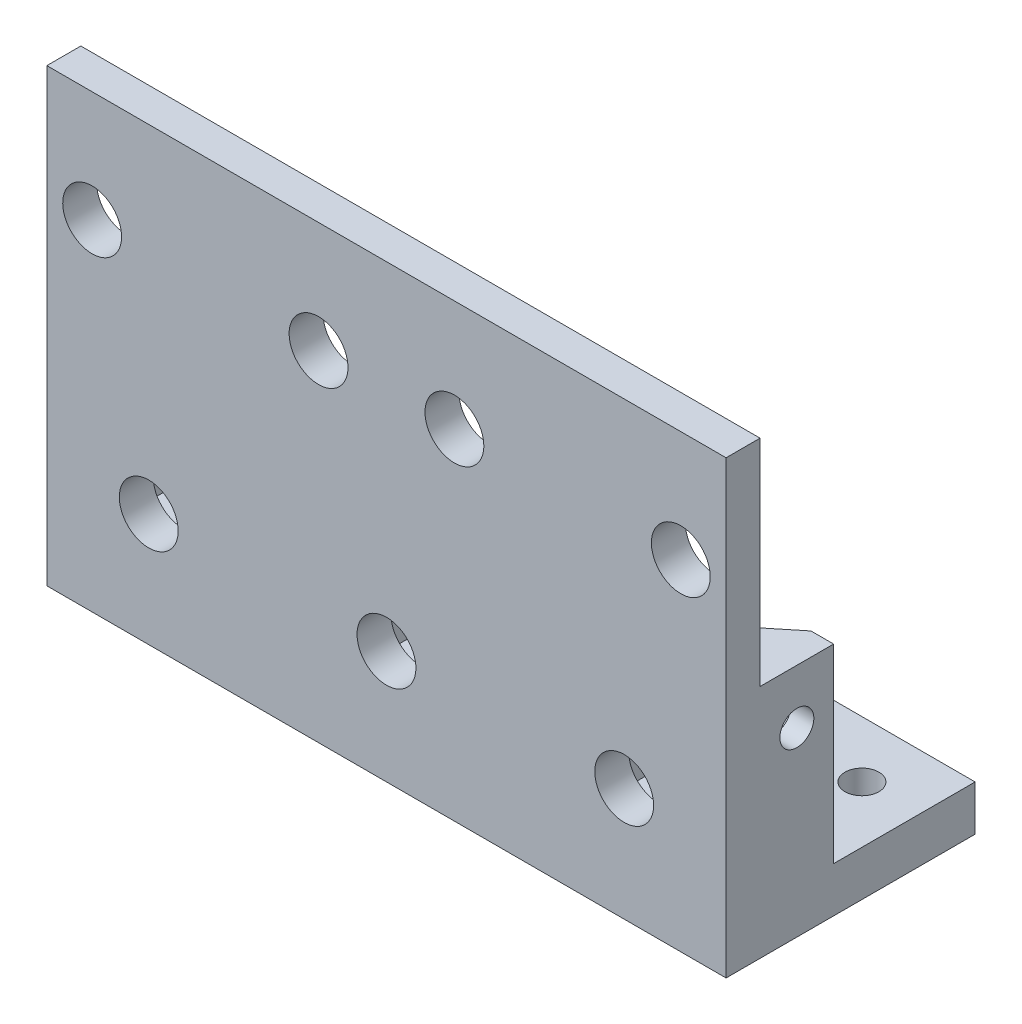
SolidWorks part; units mm, degrees
ref_plane "前视基准面" through (0, 0, 0) normal (0, 0, 1) x (1, 0, 0)
ref_plane "上视基准面" through (0, 0, 0) normal (0, 1, 0) x (1, 0, 0)
ref_plane "右视基准面" through (0, 0, 0) normal (1, 0, 0) x (0, 0, -1)
other "Configuration Table"
sketch "草图1" plane through (0, 0, 0) normal (1, 0, 0) x (0, 0, -1)
  line L1 (-1.5, 19.9) -> (1.5, 19.9)
  line L2 (-1.5, 19.9) -> (-1.5, -19.9)
  line L3 (-1.5, -19.9) -> (1.5, -19.9)
  line L4 (1.5, 19.9) -> (1.5, -0.1)
  line L5 (-1.5, 19.9) -> (1.5, -19.9) construction
  line L6 (-1.5, -19.9) -> (1.5, 19.9) construction
  line L8 (1.5, -19.9) -> (20.5, -19.9)
  line L11 (20.5, -19.9) -> (20.5, -15.9)
  line L12 (20.5, -15.9) -> (1.5, -0.1)
  point P0 (0, 0)
  dimension "D1" = 3
  dimension "D2" = 39.8
  dimension "D3" = 20
  dimension "D4" = 4
  dimension "D5" = 22
extrude "凸台-拉伸1" add sketch "草图1" along normal blind 60
ref_plane "基准面1" through (0, -15.9, 0) normal (0, -1, 0) x (-1, 0, 0)
sketch "草图2" plane through (0, -15.9, 0) normal (0, -1, 0) x (-1, 0, 0)
  line L1 (-60, 20.5) -> (-45, 20.5)
  line L2 (-60, 20.5) -> (-60, 1.5)
  line L3 (-60, 1.5) -> (-45, 1.5)
  line L4 (-45, 20.5) -> (-45, 1.5)
  line L5 (0, 20.5) -> (-15, 20.5)
  line L6 (0, 20.5) -> (0, 1.5)
  line L7 (0, 1.5) -> (-15, 1.5)
  line L8 (-15, 20.5) -> (-15, 1.5)
  line L13 (-30, 20.5) -> (-30, -1.5) construction
  line L14 (-60, 20.5) -> (0, 20.5) construction
  line L15 (-60, 1.5) -> (0, 1.5) construction
  line L16 (-60, -1.5) -> (0, -1.5) construction
  line L18 (-36, 1.5) -> (-24, 1.5)
  line L19 (-36, 1.5) -> (-36, 20.5)
  line L20 (-36, 20.5) -> (-24, 20.5)
  line L21 (-24, 1.5) -> (-24, 20.5)
  line L22 (-36, 1.5) -> (-24, 20.5) construction
  line L23 (-36, 20.5) -> (-24, 1.5) construction
  point P16 (-30, 11)
  dimension "D1" = 15
  dimension "D2" = 12
  dimension "D3" = 15
extrude "切除-拉伸1" cut sketch "草图2" against normal blind 60
hole_wizard "孔1" positions "草图3" profile "草图4" legacy end condition through all
sketch "草图3" plane through (0, 0, -1.5) normal (0, 0, -1) x (-1, 0, 0)
  line L2 (-60, -19.9) -> (0, -19.9) construction
  line L3 (-60, -15.9) -> (-60, 19.9) construction
  line L4 (0, -15.9) -> (0, 19.9) construction
  line L5 (-24, -0.1) -> (-24, -15.9) construction
  point P0 (-51, -9.9)
  point P2 (-30, -9.9)
  point P4 (-9, -9.9)
  dimension "D1" = 10
  dimension "D2" = 10
  dimension "D3" = 10
  dimension "D4" = 9
  dimension "D5" = 9
  dimension "D6" = 6
sketch "草图4" plane through (51, -9.9, -1.5) normal (1, 0, 0) x (0, 1, 0)
  line L0 (0, 0) -> (0, 3)
  line L1 (0, 3) -> (2.6, 3)
  line L2 (2.6, 3) -> (2.6, 0)
  line L3 (2.6, 0) -> (0, 0)
  line L4 (0, 110) -> (0, -10) construction
  dimension "直径" = 5.2
  dimension "深度" = 3
hole_wizard "孔2" positions "草图5" profile "草图6" legacy end condition through all
sketch "草图5" plane through (0, -19.9, 0) normal (0, -1, 0) x (-1, 0, 0)
  line L0 (-60, 20.5) -> (0, 20.5) construction
  line L1 (-60, -1.5) -> (-60, 20.5) construction
  line L2 (0, -1.5) -> (0, 20.5) construction
  point P0 (-55, 15.5)
  point P2 (-30, 15.5)
  point P4 (-5, 15.5)
  dimension "D1" = 5
  dimension "D2" = 5
  dimension "D3" = 5
  dimension "D4" = 5
  dimension "D5" = 5
sketch "草图6" plane through (55, -19.9, -15.5) normal (1, 0, 0) x (0, 0, -1)
  line L0 (0, 0) -> (0, 39.8)
  line L1 (0, 39.8) -> (1.5, 39.8)
  line L2 (1.5, 39.8) -> (1.5, 0)
  line L3 (1.5, 0) -> (0, 0)
  line L4 (0, 110) -> (0, -10) construction
  dimension "直径" = 3
  dimension "深度" = 39.8
sketch "草图7" plane through (0, 0, 0) normal (-1, 0, 0) x (0, 0, 1)
  line L0 (-1.5, -0.1) -> (-1.5, -15.9) construction
  line L1 (-1.5, -0.9) -> (-8, -0.9)
  line L2 (-1.5, -0.9) -> (-1.5, -6.9)
  line L4 (-8, -0.9) -> (-8, -6.9)
  line L5 (-14.212, -15.9) -> (14.212, -15.9) construction
  line L6 (-8, -3.9) -> (-1.5, -3.9) construction
  line L8 (-8, -6.9) -> (-8, -15.9)
  line L9 (-1.5, -15.9) -> (-20.5, -15.9) construction
  line L11 (-8, -15.9) -> (-1.5, -15.9)
  line L12 (-1.5, -6.9) -> (-1.5, -15.9)
  circle A0 centre (-4.75, -3.9) radius 1.5
  dimension "D2" = 3
  dimension "D1" = 15
  dimension "D3" = 6.5
extrude "凸台-拉伸2" add sketch "草图7" against normal blind 2
ref_plane "基准面2" through (30, 0, 0) normal (-1, 0, 0) x (0, 0, 1)
sketch "草图8" plane through (0, -0.9, 0) normal (0, 1, 0) x (1, 0, 0)
  line L0 (2, 8) -> (10, 1.5)
  line L1 (0, 8) -> (2, 8)
  line L2 (0, 8) -> (0, 1.5)
  line L3 (0, 1.5) -> (2, 1.5)
  line L5 (60, 1.5) -> (0, 1.5) construction
  line L6 (10, 1.5) -> (2, 1.5)
  dimension "D1" = 10
extrude "凸台-拉伸3" add sketch "草图8" along normal blind 1.8
hole_wizard "孔3" positions "3D草图1" profile "草图9" legacy end condition through all
sketch3d "3D草图1"
  line L0 (60, -15.9, -1.5) -> (60, 19.9, -1.5) construction
  line L1 (60, 19.9, -1.5) -> (0, 19.9, -1.5) construction
  point P0 (56, 10.1, -1.5)
  point P2 (36, 10.1, -1.5)
  point P16 (24, 10.1, -1.5)
  point P17 (4, 10.1, -1.5)
  dimension "D1" = 4
  dimension "D2" = 24
  dimension "D3" = 9.8
  dimension "D4" = 9.8
sketch "草图9" plane through (56, 10.1, -1.5) normal (1, 0, 0) x (0, 1, 0)
  line L0 (0, 0) -> (0, 3)
  line L1 (0, 3) -> (2.6, 3)
  line L2 (2.6, 3) -> (2.6, 0)
  line L3 (2.6, 0) -> (0, 0)
  line L4 (0, 110) -> (0, -10) construction
  dimension "直径" = 5.2
  dimension "深度" = 3
mirror "镜向1" about plane through (30, 0, 0) normal (-1, 0, 0) of "凸台-拉伸2", "凸台-拉伸3"
